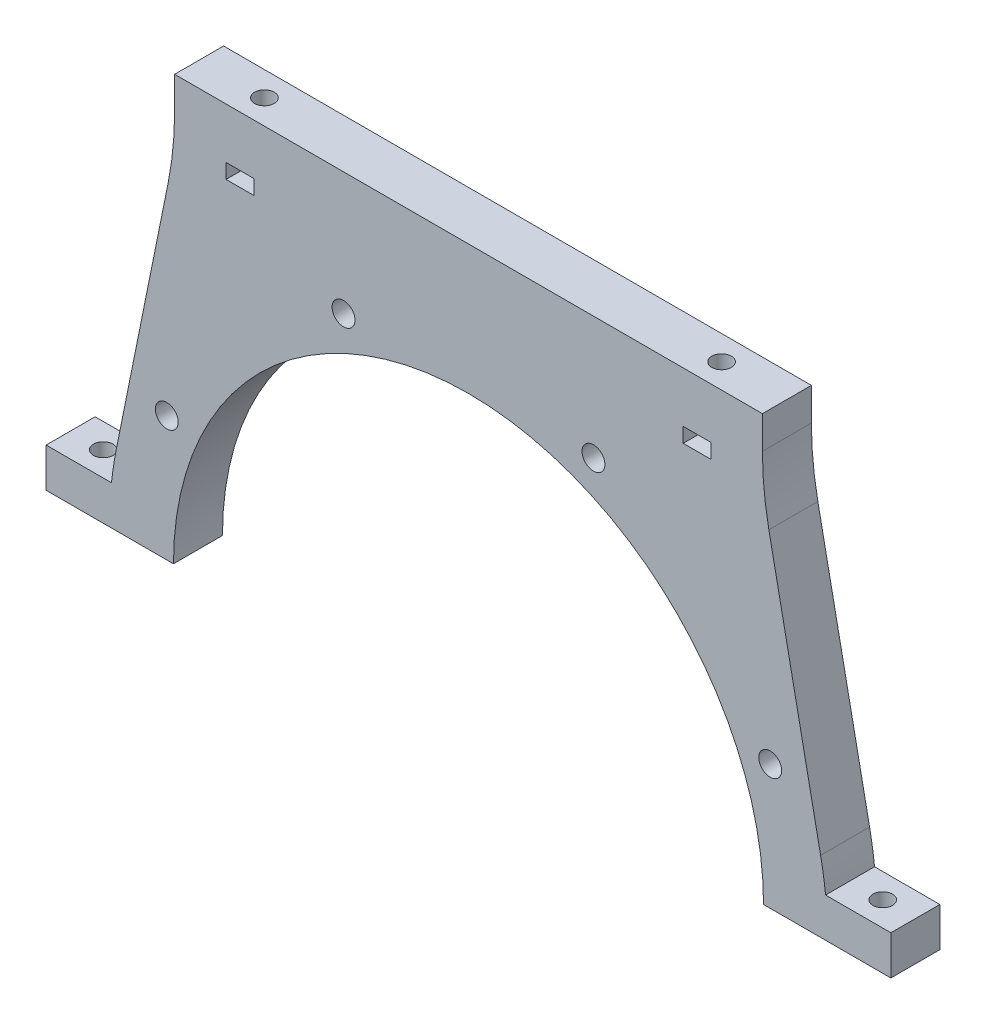
SolidWorks part; units mm, degrees
ref_plane "前视基准面" through (0, 0, 0) normal (0, 0, 1) x (1, 0, 0)
ref_plane "上视基准面" through (0, 0, 0) normal (0, 1, 0) x (1, 0, 0)
ref_plane "右视基准面" through (0, 0, 0) normal (1, 0, 0) x (0, 0, -1)
sketch "草图1" plane through (0, 0, 0) normal (0, 0, 1) x (1, 0, 0)
  line L0 (-90.35, 0) -> (-110, 0)
  line L1 (90.35, 0) -> (110, 0)
  arc A0 (90.35, 0) -> (-90.35, 0) centre (0, 0) ccw
  arc A1 (110, 0) -> (-110, 0) centre (0, 0) ccw
  dimension "D1" = 90.35
  dimension "D2" = 110
extrude "凸台-拉伸1" add sketch "草图1" along normal blind 15
sketch "草图2" plane through (0, 0, 15) normal (0, 0, 1) x (1, 0, 0)
  line L0 (0, 0) -> (0, 100) construction
  line L1 (0, 0) -> (38.2683, 92.388) construction
  circle A0 centre (0, 0) radius 100 construction
  circle A1 centre (38.2683, 92.388) radius 3.5
  circle A2 centre (92.388, 38.2683) radius 3.5
  circle A3 centre (92.388, -38.2683) radius 3.5
  circle A4 centre (38.2683, -92.388) radius 3.5
  circle A5 centre (-38.2683, -92.388) radius 3.5
  circle A6 centre (-92.388, -38.2683) radius 3.5
  circle A7 centre (-92.388, 38.2683) radius 3.5
  circle A8 centre (-38.2683, 92.388) radius 3.5
  point P23 (0, 0)
  dimension "D1" = 22.5
  dimension "D3" = 7
  dimension "D4" = 200
  dimension "D2" = 8
extrude "切除-拉伸2" cut sketch "草图2" against normal up to surface (15 mm away) up to face at (0, 50.0875, 0)
sketch "草图3" plane through (0, 0, 15) normal (0, 0, 1) x (1, 0, 0)
  line L0 (-110, 0) -> (-129.3435, 0)
  line L1 (-129.3435, 0) -> (-129.3435, 12)
  line L2 (-129.3435, 12) -> (-109.3435, 12)
  line L3 (0, 110) -> (0, 0) construction
  line L4 (129.3435, 12) -> (109.3435, 12)
  line L5 (129.3435, 0) -> (129.3435, 12)
  line L6 (110, 0) -> (129.3435, 0)
  arc A0 (110, 0) -> (-110, 0) centre (0, 0) ccw construction
  arc A1 (110, 0) -> (109.3435, 12) centre (0, 0) ccw
  arc A2 (-109.3435, 12) -> (-110, 0) centre (0, 0) ccw
  dimension "D1" = 20
  dimension "D2" = 12
extrude "凸台-拉伸2" add sketch "草图3" against normal up to surface (15 mm away) up to face at (95.888, 38.2683, 0)
ref_plane "基准面1" through (0, 0, 0) normal (-1, 0, 0) x (0, 0, 1)
sketch "草图4" plane through (0, 12, 0) normal (0, 1, 0) x (1, 0, 0)
  line L0 (-129.3435, 0) -> (-129.3435, -15) construction
  line L1 (-129.3435, 0) -> (-109.3435, 0) construction
  circle A0 centre (-119.3435, -7.5) radius 3
  dimension "D1" = 6
  dimension "D2" = 10
  dimension "D3" = 7.5
extrude "切除-拉伸3" cut sketch "草图4" against normal up to next
mirror "镜向1" about plane through (0, 0, 0) normal (-1, 0, 0) of "切除-拉伸3"
sketch "草图5" plane through (0, 0, 15) normal (0, 0, 1) x (1, 0, 0)
  line L0 (0, 32.7895) -> (0, -32.7895) construction
  line L1 (-90, 130) -> (90, 130)
  line L2 (-90, 130) -> (-90, 110)
  line L4 (90, 130) -> (90, 110)
  line L5 (-90, 130) -> (0, 120) construction
  line L6 (0, 120) -> (90, 130) construction
  line L7 (-90, 110) -> (-107.8218, 21.7822)
  line L8 (90, 110) -> (107.8218, 21.7822)
  arc A0 (109.3435, 12) -> (-109.3435, 12) centre (0, 0) ccw construction
  arc A1 (107.8218, 21.7822) -> (-107.8218, 21.7822) centre (0, 0) ccw
  point P0 (0, 120)
  dimension "D1" = 120
  dimension "D2" = 20
  dimension "D3" = 180
extrude "凸台-拉伸3" add sketch "草图5" against normal up to surface (15 mm away) up to face at (95.888, 38.2683, 0)
fillet "圆角2" radius 100 1 edges at (90, 110, 7.5)
fillet "圆角3" radius 100 1 edges at (-90, 110, 7.5)
sketch "草图6" plane through (0, 130, 0) normal (0, 1, 0) x (1, 0, 0)
  line L0 (-90, 0) -> (-90, -15) construction
  line L1 (-90, 0) -> (90, 0) construction
  circle A0 centre (-70, -7.5) radius 3
  dimension "D1" = 6
  dimension "D2" = 20
  dimension "D3" = 7.5
extrude "切除-拉伸4" cut sketch "草图6" against normal blind 30
ref_plane "基准面2" through (0, 110, 0) normal (0, 1, 0) x (1, 0, 0)
sketch "草图7" plane through (0, 110, 0) normal (0, 1, 0) x (1, 0, 0)
  line L0 (-74.25, -9.9537) -> (-74.25, -15)
  line L1 (-70, -2.5925) -> (-74.25, -5.0463)
  line L2 (-74.25, -5.0463) -> (-74.25, -9.9537)
  line L5 (-65.75, -9.9537) -> (-65.75, -5.0463)
  line L6 (-65.75, -5.0463) -> (-70, -2.5925)
  line L7 (90, -15) -> (-90, -15) construction
  line L8 (-74.25, -15) -> (-65.75, -15)
  line L9 (-65.75, -15) -> (-65.75, -9.9537)
  line L11 (-67.875, -11.1806) -> (-65.75, -9.9537) [skipped]
  line L12 (-74.25, -9.9537) -> (-72.125, -11.1806) [skipped]
  arc A0 (-65.75, -7.5) -> (-74.25, -7.5) centre (-70, -7.5) ccw construction
  dimension "D1" = 8.5
extrude "切除-拉伸5" cut sketch "草图7" along normal blind 4.5
mirror "镜向2" about plane through (0, 0, 0) normal (-1, 0, 0) of "切除-拉伸4", "切除-拉伸5"
